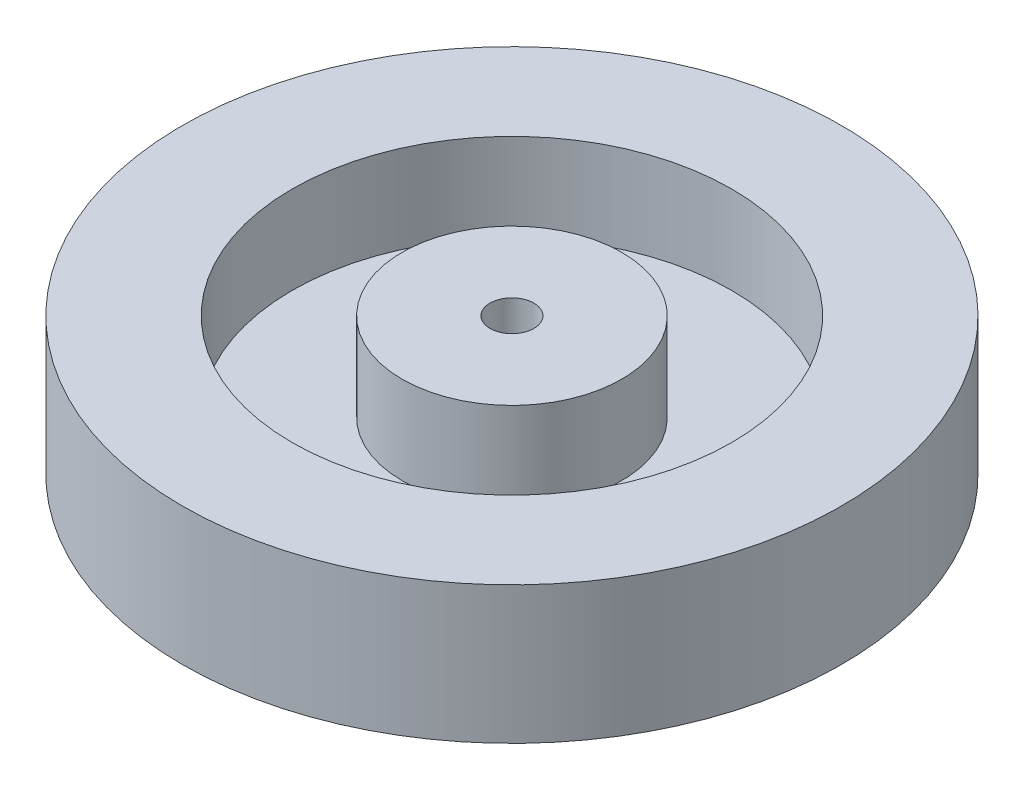
SolidWorks part; units mm, degrees
ref_plane "Front Plane" through (0, 0, 0) normal (0, 0, 1) x (1, 0, 0)
ref_plane "Top Plane" through (0, 0, 0) normal (0, 1, 0) x (1, 0, 0)
ref_plane "Right Plane" through (0, 0, 0) normal (1, 0, 0) x (0, 0, -1)
sketch "Sketch1" plane through (0, 0, 0) normal (0, 1, 0) x (1, 0, 0)
  circle A0 centre (0, 0) radius 60
extrude "Boss-Extrude1" add sketch "Sketch1" along normal blind 25
sketch "Sketch2" plane through (0, 25, 0) normal (0, 1, 0) x (1, 0, 0)
  circle A0 centre (0, 0) radius 40
  circle A1 centre (0, 0) radius 20
extrude "Cut-Extrude1" cut sketch "Sketch2" against normal blind 16
sketch "Sketch3" plane through (0, 0, 0) normal (0, -1, 0) x (1, 0, 0)
  circle A0 centre (0, 0) radius 20
extrude "Boss-Extrude2" add sketch "Sketch3" along normal blind 16
sketch "Sketch4" plane through (0, -16, 0) normal (0, -1, 0) x (1, 0, 0)
  circle A0 centre (0, 0) radius 4
extrude "Cut-Extrude2" cut sketch "Sketch4" against normal blind 41
